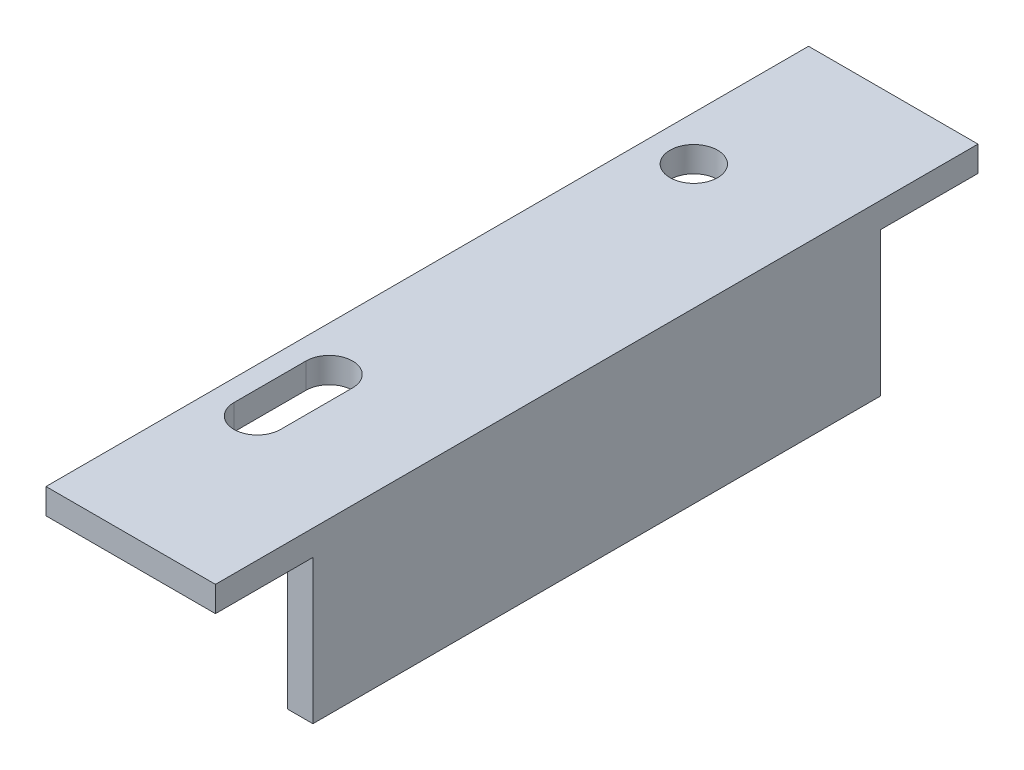
SolidWorks part; units mm, degrees
ref_plane "Front Plane" through (0, 0, 0) normal (0, 0, 1) x (1, 0, 0)
ref_plane "Top Plane" through (0, 0, 0) normal (0, 1, 0) x (1, 0, 0)
ref_plane "Right Plane" through (0, 0, 0) normal (1, 0, 0) x (0, 0, -1)
sketch "Sketch1" plane through (0, 0, 0) normal (0, 0, 1) x (1, 0, 0)
  line L0 (0, 0) -> (40, 0)
  line L1 (40, 0) -> (40, -40)
  line L2 (0, -6) -> (34, -6)
  line L3 (34, -6) -> (34, -40)
  line L4 (0, -6) -> (0, 0)
  line L5 (34, -40) -> (40, -40)
  dimension "D1" = 40
  dimension "D2" = 40
  dimension "D4" = 6
  dimension "D3" = 6
extrude "Boss-Extrude1" add sketch "Sketch1" against normal blind 180
sketch "Sketch2" plane through (34, 0, 0) normal (-1, 0, 0) x (0, 0, 1)
  line L0 (-180, -40) -> (0, -40) construction
  line L1 (0, -6) -> (-23, -6)
  line L2 (0, -6) -> (0, -40)
  line L3 (0, -40) -> (-23, -40)
  line L4 (-23, -6) -> (-23, -40)
  line L6 (-180, -6) -> (-157, -6)
  line L7 (-180, -6) -> (-180, -40)
  line L8 (-180, -40) -> (-157, -40)
  line L9 (-157, -6) -> (-157, -40)
  dimension "D1" = 23
  dimension "D2" = 23
extrude "Cut-Extrude1" cut sketch "Sketch2" against normal blind 200
sketch "Sketch3" plane through (0, 0, 0) normal (0, 1, 0) x (1, 0, 0)
  line L1 (40, 180) -> (0, 180) construction
  line L2 (10.52, 56.35) -> (10.52, 39.35) construction
  line L5 (40, 180) -> (40, 0) construction
  line L6 (16.02, 56.35) -> (16.02, 39.35)
  line L7 (5.02, 56.35) -> (5.02, 39.35)
  line L8 (40, 0) -> (0, 0) construction
  circle A0 centre (10.52, 142.4) radius 5.625
  arc A2 (16.02, 56.35) -> (5.02, 56.35) centre (10.52, 56.35) ccw
  arc A3 (5.02, 39.35) -> (16.02, 39.35) centre (10.52, 39.35) ccw
  point P6 (10.52, 47.85)
  point P11 (10.52, 61.85)
  point P14 (10.52, 33.85)
  dimension "D3" = 11.25
  dimension "D6" = 28
  dimension "D1" = 29.48
  dimension "D2" = 37.6
  dimension "D4" = 11
  dimension "D5" = 17
  dimension "D7" = 33.85
  dimension "D8" = 23.98
extrude "Cut-Extrude2" cut sketch "Sketch3" against normal blind 200
